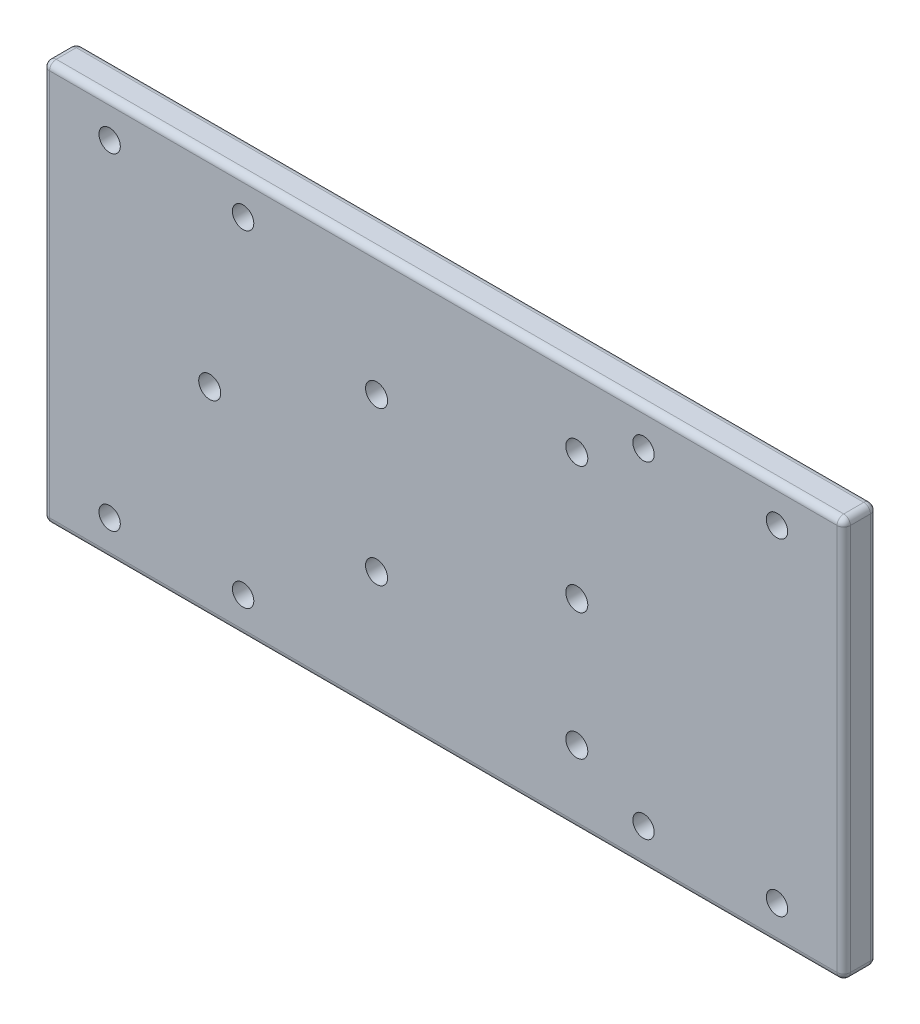
SolidWorks part; units mm, degrees
ref_plane "前视基准面" through (0, 0, 0) normal (0, 0, 1) x (1, 0, 0)
ref_plane "上视基准面" through (0, 0, 0) normal (0, 1, 0) x (1, 0, 0)
ref_plane "右视基准面" through (0, 0, 0) normal (1, 0, 0) x (0, 0, -1)
other "Configuration Table"
sketch "草图1" plane through (0, 0, 0) normal (0, 0, 1) x (1, 0, 0)
  line L0 (12, -49) -> (12, 0) construction
  line L1 (20, 5.5) -> (-100, 5.5)
  line L2 (20, 5.5) -> (20, -54.5)
  line L3 (20, -54.5) -> (-100, -54.5)
  line L4 (-100, 5.5) -> (-100, -54.5)
  line L5 (12, -52.5) -> (12, -45.5) construction
  line L6 (12, -3.5) -> (12, 3.5) construction
  line L7 (12, -24.5) -> (23.0806, -24.5) construction
  point P12 (12, -24.5)
  dimension "D3" = 20
  dimension "D1" = 60
  dimension "D2" = 120
extrude "凸台-拉伸1" add sketch "草图1" along normal blind 5
sketch "草图2" plane through (0, 0, 5) normal (0, 0, 1) x (1, 0, 0)
  circle A0 centre (-50, -13) radius 1.65
  circle A1 centre (-75, -24.5) radius 1.65
  circle A3 centre (-50, -36) radius 1.65
  dimension "D1" = 3.3
extrude "切除-拉伸1" cut sketch "草图2" against normal up to next
sketch "草图4" plane through (0, 0, 0) normal (0, 0, -1) x (-1, 0, 0)
  circle A0 centre (90, 0) radius 1.6
  circle A1 centre (70, 0) radius 1.6
  circle A2 centre (70, -49) radius 1.6
  circle A3 centre (90, -49) radius 1.6
  circle A4 centre (10, -49) radius 1.6
  circle A5 centre (-10, -49) radius 1.6
  circle A6 centre (-10, 0) radius 1.6
  circle A7 centre (10, 0) radius 1.6
  dimension "D1" = 3.2
extrude "切除-拉伸2" cut sketch "草图4" against normal up to next
sketch "草图5" plane through (0, 0, 5) normal (0, 0, 1) x (1, 0, 0)
  line L0 (-20, -54.5) -> (-20, 5.5) construction
  line L1 (-100, -54.5) -> (20, -54.5) construction
  line L2 (20, 5.5) -> (-100, 5.5) construction
  line L3 (20, -54.5) -> (20, 5.5) construction
  line L4 (-20, -24.5) -> (20, -24.5) construction
  circle A0 centre (-20, -43.5) radius 1.65
  circle A1 centre (-20, -24.5) radius 1.65
  circle A2 centre (-20, -5.5) radius 1.65
  dimension "D4" = 3.3
  dimension "D1" = 40
  dimension "D2" = 11
  dimension "D3" = 11
extrude "切除-拉伸3" cut sketch "草图5" against normal up to next
fillet "圆角1" radius 1 12 edges at (-40, -54.5, 5) (-40, -54.5, 0) (-100, -24.5, 5) (-100, -54.5, 2.5) (-100, -24.5, 0) (-40, 5.5, 5) (-100, 5.5, 2.5) (-40, 5.5, 0) (20, -54.5, 2.5) (20, -24.5, 5) (20, 5.5, 2.5) (20, -24.5, 0)
